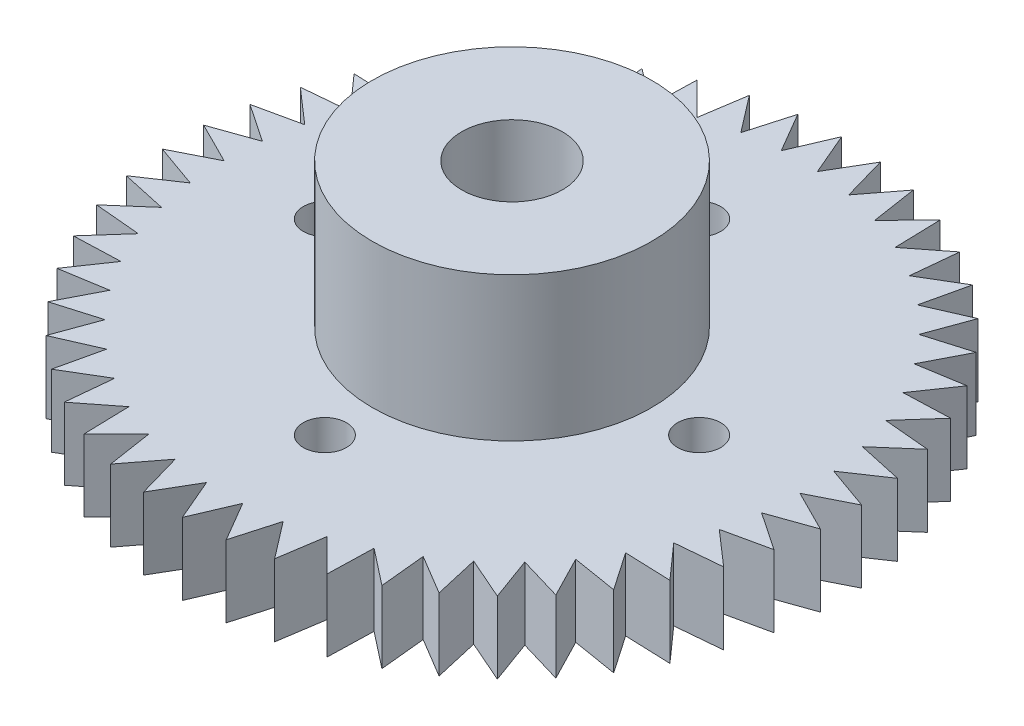
SolidWorks part; units mm, degrees
ref_plane "前视基准面" through (0, 0, 0) normal (0, 0, 1) x (1, 0, 0)
ref_plane "上视基准面" through (0, 0, 0) normal (0, 1, 0) x (1, 0, 0)
ref_plane "右视基准面" through (0, 0, 0) normal (1, 0, 0) x (0, 0, -1)
other "Configuration Table"
sketch "草图1" plane through (0, 0, 0) normal (0, 1, 0) x (1, 0, 0)
  circle A0 centre (0, 0) radius 20
  dimension "D1" = 40
extrude "凸台-拉伸1" add sketch "草图1" along normal blind 5
sketch "草图2" plane through (0, 5, 0) normal (0, 1, 0) x (1, 0, 0)
  circle A0 centre (0, 0) radius 9.7
  dimension "D1" = 19.4
extrude "凸台-拉伸2" add sketch "草图2" along normal blind 10
sketch "草图3" plane through (0, 15, 0) normal (0, 1, 0) x (1, 0, 0)
  circle A0 centre (0, 0) radius 3.5
  dimension "D1" = 7
extrude "切除-拉伸1" cut sketch "草图3" against normal blind 15
sketch "草图6" plane through (0, 5, 0) normal (0, 1, 0) x (1, 0, 0)
  circle A0 centre (-13, 0) radius 1.5
  circle A1 centre (0, 13) radius 1.5
  circle A2 centre (13, 0) radius 1.5
  circle A3 centre (0, -13) radius 1.5
  point P12 (0, 0)
  dimension "D2" = 3
  dimension "D1" = 13
  dimension "D3" = 4
extrude "切除-拉伸2" cut sketch "草图6" against normal blind 15
sketch "草图9" plane through (0, 5, 0) normal (0, 1, 0) x (1, 0, 0)
sketch "草图12" plane through (0, 0, 0) normal (0, 1, 0) x (1, 0, 0)
  line L0 (-1.2558, 19.9605) -> (0, 22.9)
  line L1 (0, 22.9) -> (1.2558, 19.9605)
  line L2 (0, 0) -> (-1.2558, 19.9605) construction
  line L3 (0, 0) -> (1.2558, 19.9605) construction
  line L4 (0, 0) -> (0, 28.0804) construction
  line L5 (2.8701, 22.7194) -> (3.7476, 19.6457)
  line L6 (1.2558, 19.9605) -> (2.8701, 22.7194)
  line L7 (5.695, 22.1806) -> (6.1803, 19.0211)
  line L8 (3.7476, 19.6457) -> (5.695, 22.1806)
  line L9 (8.4301, 21.2919) -> (8.5156, 18.0965)
  line L10 (6.1803, 19.0211) -> (8.4301, 21.2919)
  line L11 (11.0322, 20.0674) -> (10.7165, 16.8866)
  line L12 (8.5156, 18.0965) -> (11.0322, 20.0674)
  line L13 (13.4603, 18.5265) -> (12.7485, 15.4103)
  line L14 (10.7165, 16.8866) -> (13.4603, 18.5265)
  line L15 (15.6761, 16.6934) -> (14.5794, 13.6909)
  line L16 (12.7485, 15.4103) -> (15.6761, 16.6934)
  line L17 (17.6448, 14.597) -> (16.1803, 11.7557)
  line L18 (14.5794, 13.6909) -> (17.6448, 14.597)
  line L19 (19.3351, 12.2704) -> (17.5261, 9.6351)
  line L20 (16.1803, 11.7557) -> (19.3351, 12.2704)
  line L21 (20.7205, 9.7503) -> (18.5955, 7.3625)
  line L22 (17.5261, 9.6351) -> (20.7205, 9.7503)
  line L23 (21.7792, 7.0765) -> (19.3717, 4.9738)
  line L24 (18.5955, 7.3625) -> (21.7792, 7.0765)
  line L25 (22.4944, 4.291) -> (19.8423, 2.5067)
  line L26 (19.3717, 4.9738) -> (22.4944, 4.291)
  line L27 (22.8548, 1.4379) -> (20, 0)
  line L28 (19.8423, 2.5067) -> (22.8548, 1.4379)
  line L29 (22.8548, -1.4379) -> (19.8423, -2.5067)
  line L30 (20, 0) -> (22.8548, -1.4379)
  line L31 (22.4944, -4.291) -> (19.3717, -4.9738)
  line L32 (19.8423, -2.5067) -> (22.4944, -4.291)
  line L33 (21.7792, -7.0765) -> (18.5955, -7.3625)
  line L34 (19.3717, -4.9738) -> (21.7792, -7.0765)
  line L35 (20.7205, -9.7503) -> (17.5261, -9.6351)
  line L36 (18.5955, -7.3625) -> (20.7205, -9.7503)
  line L37 (19.3351, -12.2704) -> (16.1803, -11.7557)
  line L38 (17.5261, -9.6351) -> (19.3351, -12.2704)
  line L39 (17.6448, -14.597) -> (14.5794, -13.6909)
  line L40 (16.1803, -11.7557) -> (17.6448, -14.597)
  line L41 (15.6761, -16.6934) -> (12.7485, -15.4103)
  line L42 (14.5794, -13.6909) -> (15.6761, -16.6934)
  line L43 (13.4603, -18.5265) -> (10.7165, -16.8866)
  line L44 (12.7485, -15.4103) -> (13.4603, -18.5265)
  line L45 (11.0322, -20.0674) -> (8.5156, -18.0965)
  line L46 (10.7165, -16.8866) -> (11.0322, -20.0674)
  line L47 (8.4301, -21.2919) -> (6.1803, -19.0211)
  line L48 (8.5156, -18.0965) -> (8.4301, -21.2919)
  line L49 (5.695, -22.1806) -> (3.7476, -19.6457)
  line L50 (6.1803, -19.0211) -> (5.695, -22.1806)
  line L51 (2.8701, -22.7194) -> (1.2558, -19.9605)
  line L52 (3.7476, -19.6457) -> (2.8701, -22.7194)
  line L53 (0, -22.9) -> (-1.2558, -19.9605)
  line L54 (1.2558, -19.9605) -> (0, -22.9)
  line L55 (-2.8701, -22.7194) -> (-3.7476, -19.6457)
  line L56 (-1.2558, -19.9605) -> (-2.8701, -22.7194)
  line L57 (-5.695, -22.1806) -> (-6.1803, -19.0211)
  line L58 (-3.7476, -19.6457) -> (-5.695, -22.1806)
  line L59 (-8.4301, -21.2919) -> (-8.5156, -18.0965)
  line L60 (-6.1803, -19.0211) -> (-8.4301, -21.2919)
  line L61 (-11.0322, -20.0674) -> (-10.7165, -16.8866)
  line L62 (-8.5156, -18.0965) -> (-11.0322, -20.0674)
  line L63 (-13.4603, -18.5265) -> (-12.7485, -15.4103)
  line L64 (-10.7165, -16.8866) -> (-13.4603, -18.5265)
  line L65 (-15.6761, -16.6934) -> (-14.5794, -13.6909)
  line L66 (-12.7485, -15.4103) -> (-15.6761, -16.6934)
  line L67 (-17.6448, -14.597) -> (-16.1803, -11.7557)
  line L68 (-14.5794, -13.6909) -> (-17.6448, -14.597)
  line L69 (-19.3351, -12.2704) -> (-17.5261, -9.6351)
  line L70 (-16.1803, -11.7557) -> (-19.3351, -12.2704)
  line L71 (-20.7205, -9.7503) -> (-18.5955, -7.3625)
  line L72 (-17.5261, -9.6351) -> (-20.7205, -9.7503)
  line L73 (-21.7792, -7.0765) -> (-19.3717, -4.9738)
  line L74 (-18.5955, -7.3625) -> (-21.7792, -7.0765)
  line L75 (-22.4944, -4.291) -> (-19.8423, -2.5067)
  line L76 (-19.3717, -4.9738) -> (-22.4944, -4.291)
  line L77 (-22.8548, -1.4379) -> (-20, 0)
  line L78 (-19.8423, -2.5067) -> (-22.8548, -1.4379)
  line L79 (-22.8548, 1.4379) -> (-19.8423, 2.5067)
  line L80 (-20, 0) -> (-22.8548, 1.4379)
  line L81 (-22.4944, 4.291) -> (-19.3717, 4.9738)
  line L82 (-19.8423, 2.5067) -> (-22.4944, 4.291)
  line L83 (-21.7792, 7.0765) -> (-18.5955, 7.3625)
  line L84 (-19.3717, 4.9738) -> (-21.7792, 7.0765)
  line L85 (-20.7205, 9.7503) -> (-17.5261, 9.6351)
  line L86 (-18.5955, 7.3625) -> (-20.7205, 9.7503)
  line L87 (-19.3351, 12.2704) -> (-16.1803, 11.7557)
  line L88 (-17.5261, 9.6351) -> (-19.3351, 12.2704)
  line L89 (-17.6448, 14.597) -> (-14.5794, 13.6909)
  line L90 (-16.1803, 11.7557) -> (-17.6448, 14.597)
  line L91 (-15.6761, 16.6934) -> (-12.7485, 15.4103)
  line L92 (-14.5794, 13.6909) -> (-15.6761, 16.6934)
  line L93 (-13.4603, 18.5265) -> (-10.7165, 16.8866)
  line L94 (-12.7485, 15.4103) -> (-13.4603, 18.5265)
  line L95 (-11.0322, 20.0674) -> (-8.5156, 18.0965)
  line L96 (-10.7165, 16.8866) -> (-11.0322, 20.0674)
  line L97 (-8.4301, 21.2919) -> (-6.1803, 19.0211)
  line L98 (-8.5156, 18.0965) -> (-8.4301, 21.2919)
  line L99 (-5.695, 22.1806) -> (-3.7476, 19.6457)
  line L100 (-6.1803, 19.0211) -> (-5.695, 22.1806)
  line L101 (-2.8701, 22.7194) -> (-1.2558, 19.9605)
  line L102 (-3.7476, 19.6457) -> (-2.8701, 22.7194)
  circle A0 centre (0, 0) radius 20 construction
  point P4 (0, 20)
  point P158 (0, 0)
  dimension "D1" = 2.9
  dimension "D2" = 3.6
  dimension "D3" = 3.6
  dimension "D4" = 50
extrude "凸台-拉伸3" add sketch "草图12" along normal blind 5
sketch "草图13" plane through (0, 15, 0) normal (0, 1, 0) x (1, 0, 0)
  circle A0 centre (0, 13) radius 1.5
  circle A1 centre (13, 0) radius 1.5
  circle A2 centre (0, -13) radius 1.5
  circle A3 centre (-13, 0) radius 1.5
  point P12 (0, 0)
  dimension "D2" = 3
  dimension "D1" = 13
  dimension "D3" = 4
extrude "切除-拉伸3" cut sketch "草图13" against normal through all
